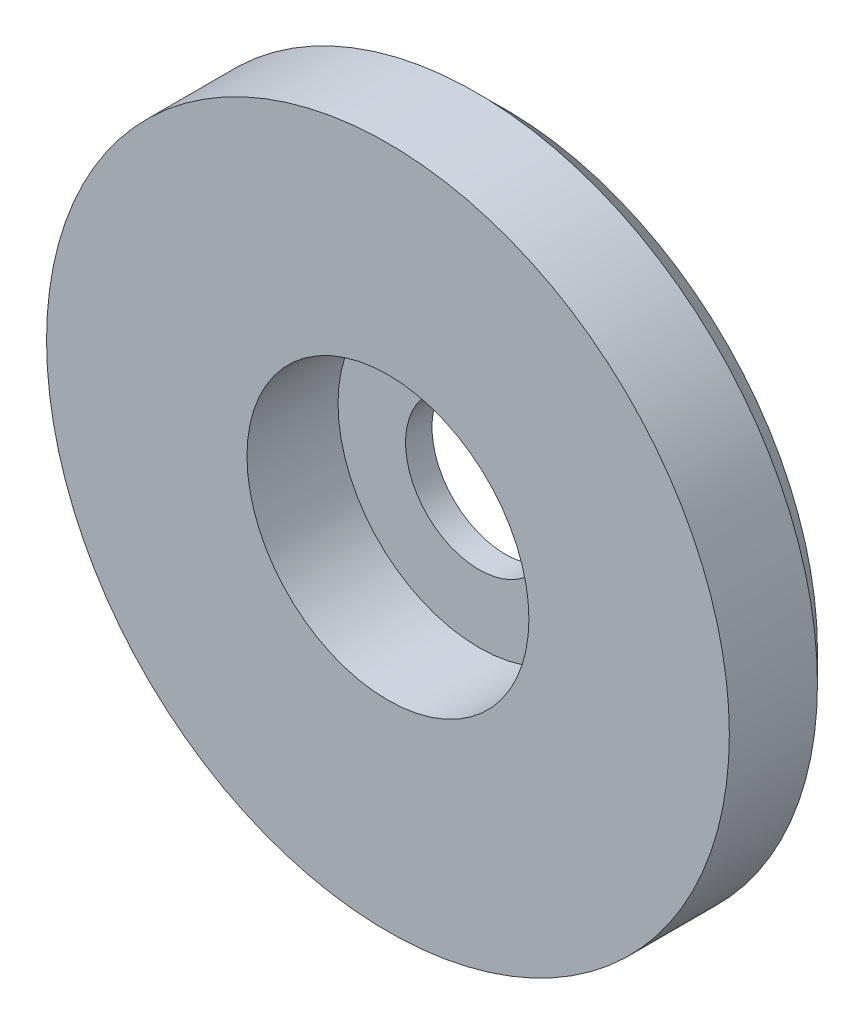
SolidWorks part; units mm, degrees
ref_plane "Front Plane" through (0, 0, 0) normal (0, 0, 1) x (1, 0, 0)
ref_plane "Top Plane" through (0, 0, 0) normal (0, 1, 0) x (1, 0, 0)
ref_plane "Right Plane" through (0, 0, 0) normal (1, 0, 0) x (0, 0, -1)
sketch "Sketch1" plane through (0, 0, 0) normal (0, 0, 1) x (1, 0, 0)
  circle A0 centre (0, 0) radius 23.25
  dimension "D1" = 46.5
extrude "Boss-Extrude1" add sketch "Sketch1" along normal blind 8
sketch "Sketch2" plane through (0, 0, 8) normal (0, 0, 1) x (1, 0, 0)
  circle A0 centre (0, 0) radius 9.6
  dimension "D1" = 19.2
extrude "Cut-Extrude1" cut sketch "Sketch2" against normal blind 6.2
sketch "Sketch3" plane through (0, 0, 1.8) normal (0, 0, 1) x (1, 0, 0)
  circle A0 centre (0, 0) radius 5
  dimension "D1" = 10
extrude "Cut-Extrude2" cut sketch "Sketch3" against normal up to surface (1.8 mm away) up to face at (23.25, 0, 0)
chamfer "Chamfer1" distance 2 angle 45 1 edges at (23.25, 0, 0)
